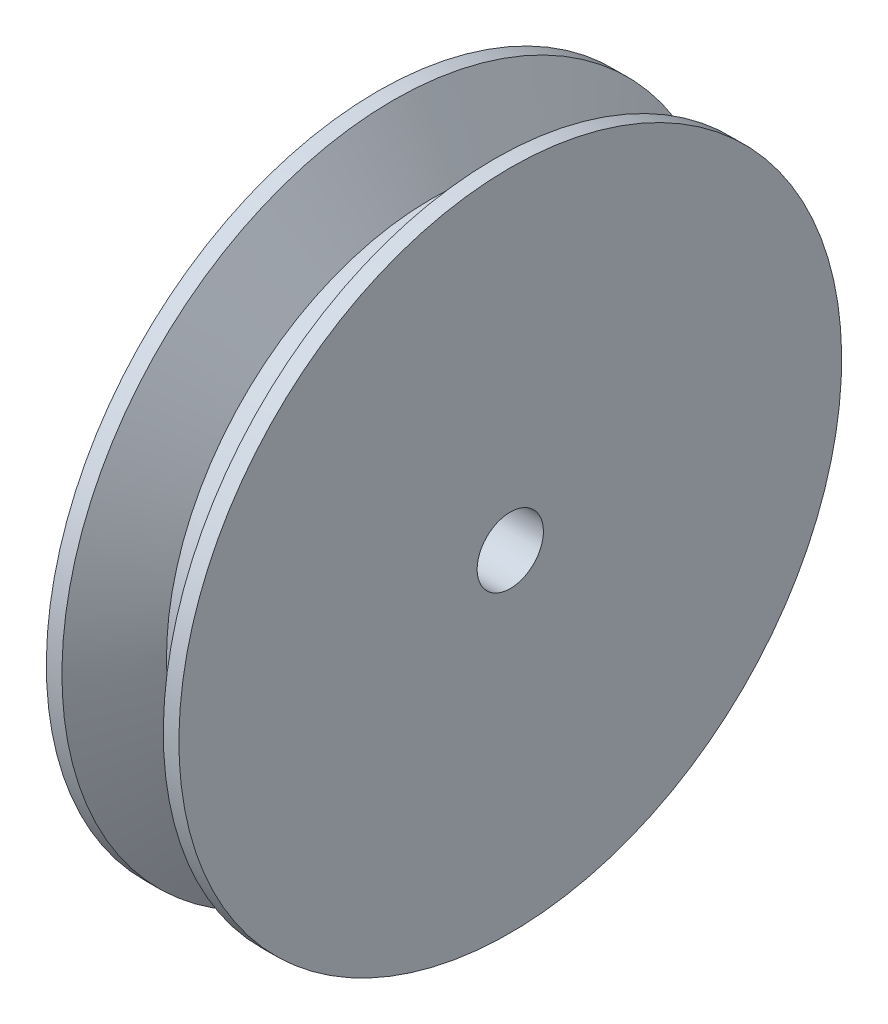
SolidWorks part; units mm, degrees
ref_plane "Front Plane" through (0, 0, 0) normal (0, 0, 1) x (1, 0, 0)
ref_plane "Top Plane" through (0, 0, 0) normal (0, 1, 0) x (1, 0, 0)
ref_plane "Right Plane" through (0, 0, 0) normal (1, 0, 0) x (0, 0, -1)
sketch "Sketch1" plane through (0, 0, 0) normal (0, 0, 1) x (1, 0, 0)
  line L0 (0, -16) -> (0, 16) construction
  line L1 (-3.0594, 20) -> (-0.75, 16)
  line L2 (-0.75, 16) -> (0.75, 16)
  line L4 (4, 0) -> (-4, 0)
  line L5 (-4, 0) -> (-4, 20)
  line L6 (-4, 20) -> (-3.0594, 20)
  line L7 (4, 20) -> (3.0594, 20)
  line L8 (4, 0) -> (4, 20)
  line L9 (3.0594, 20) -> (0.75, 16)
  point P4 (0, 0)
  dimension "D1" = 8
  dimension "D2" = 16
  dimension "D3" = 20
  dimension "D4" = 1.5
  dimension "D5" = 60
revolve "Revolve1" add sketch "Sketch1" angle 360 about L4
sketch "Sketch2" plane through (-4, 0, 0) normal (-1, 0, 0) x (0, 0, 1)
  circle A0 centre (0, 0) radius 5
  dimension "D1" = 10
extrude "Boss-Extrude1" add sketch "Sketch2" along normal blind 6
sketch "Sketch3" plane through (-10, 0, 0) normal (-1, 0, 0) x (0, 0, 1)
  circle A0 centre (0, 0) radius 2
  dimension "D1" = 4
extrude "Cut-Extrude1" cut sketch "Sketch3" against normal through all
fillet "Fillet1" radius 0.5 2 edges at (-10, -5, 0) (-4, -5, 0)
sketch "Sketch4" plane through (0, 0, 0) normal (0, 0, 1) x (1, 0, 0)
  line L0 (-4, 20) -> (-4, -20) construction
  circle A0 centre (-7, 0) radius 1
  point P6 (0, 0)
  dimension "D1" = 2
  dimension "D2" = 3
extrude "Cut-Extrude2" cut sketch "Sketch4" against normal through all both and the other way through all
